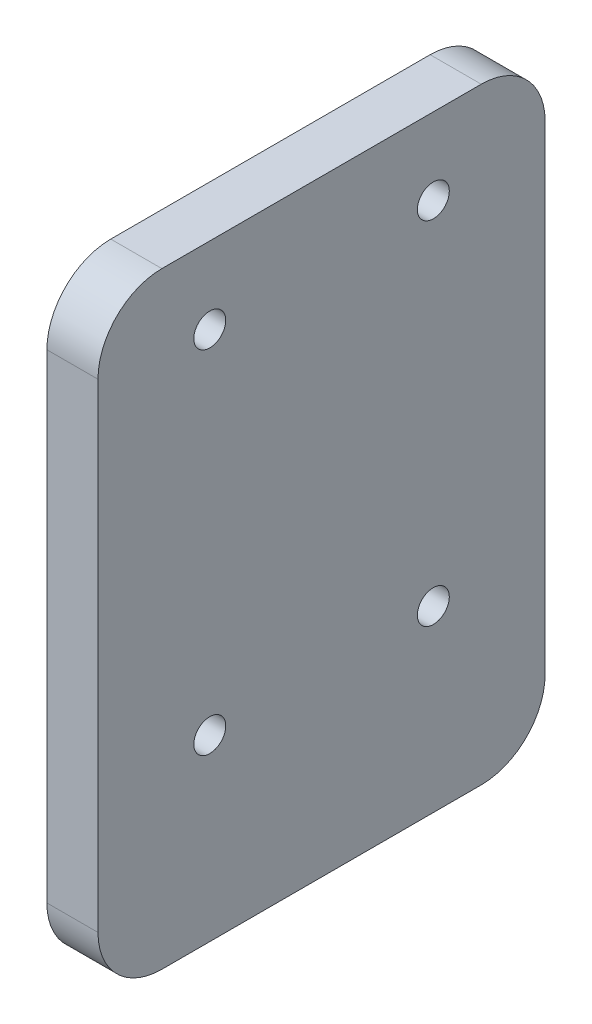
SolidWorks part; units mm, degrees
material "Q235"
ref_plane "前视基准面" through (0, 0, 0) normal (0, 0, 1) x (1, 0, 0)
ref_plane "上视基准面" through (0, 0, 0) normal (0, 1, 0) x (1, 0, 0)
ref_plane "右视基准面" through (0, 0, 0) normal (1, 0, 0) x (0, 0, -1)
sketch "草图1" plane through (0, 0, 0) normal (1, 0, 0) x (0, 0, -1)
  line L0 (-35, 47.5) -> (35, -47.5) construction
  line L1 (-35, 47.5) -> (35, 47.5)
  line L2 (-35, 47.5) -> (-35, -47.5)
  line L3 (-35, -47.5) -> (35, -47.5)
  line L4 (35, 47.5) -> (35, -47.5)
  dimension "D1" = 70
  dimension "D2" = 95
extrude "凸台-拉伸1" add sketch "草图1" along normal blind 8
hole_wizard "M6 螺纹孔1" positions "草图2" profile "草图3" tap size "M6" standard "GB"
sketch "草图2" plane through (8, 0, 0) normal (1, 0, 0) x (0, 0, -1)
  line L0 (0, 47.5) -> (0, -47.5) construction
  line L1 (35, 47.5) -> (-35, 47.5) construction
  line L2 (-35, -47.5) -> (35, -47.5) construction
  point P0 (-17.5, 35.5)
  point P2 (17.5, 35.5)
  point P4 (-17.5, -19.5)
  point P6 (17.5, -19.5)
  dimension "D1" = 35
  dimension "D2" = 55
  dimension "D3" = 12
sketch "草图3" plane through (8, 35.5, 17.5) normal (0, 1, 0) x (0, 0, -1)
  line L0 (0, 0) -> (0, 18.5022)
  line L1 (0, 18.5022) -> (2.5, 17)
  line L2 (2.5, 17) -> (2.5, 0)
  line L5 (2.5, 0) -> (0, 0)
  line L10 (0, 18.5022) -> (-2.5, 17) construction
  line L11 (0, -6.35) -> (0, 107.95) construction
  dimension "螺纹孔钻头直径" = 5
  dimension "螺纹孔钻头深度" = 17
  dimension "导头角度" = 118
cosmetic thread "孔螺蚊线1" parameters "D1"=8, "D2"=6
cosmetic thread "孔螺蚊线2" parameters "D1"=8, "D2"=6
cosmetic thread "孔螺蚊线3" parameters "D1"=8, "D2"=6
cosmetic thread "孔螺蚊线4" parameters "D1"=8, "D2"=6
fillet "圆角1" radius 10 4 edges at (4, -47.5, 35) (4, -47.5, -35) (4, 47.5, -35) (4, 47.5, 35)
